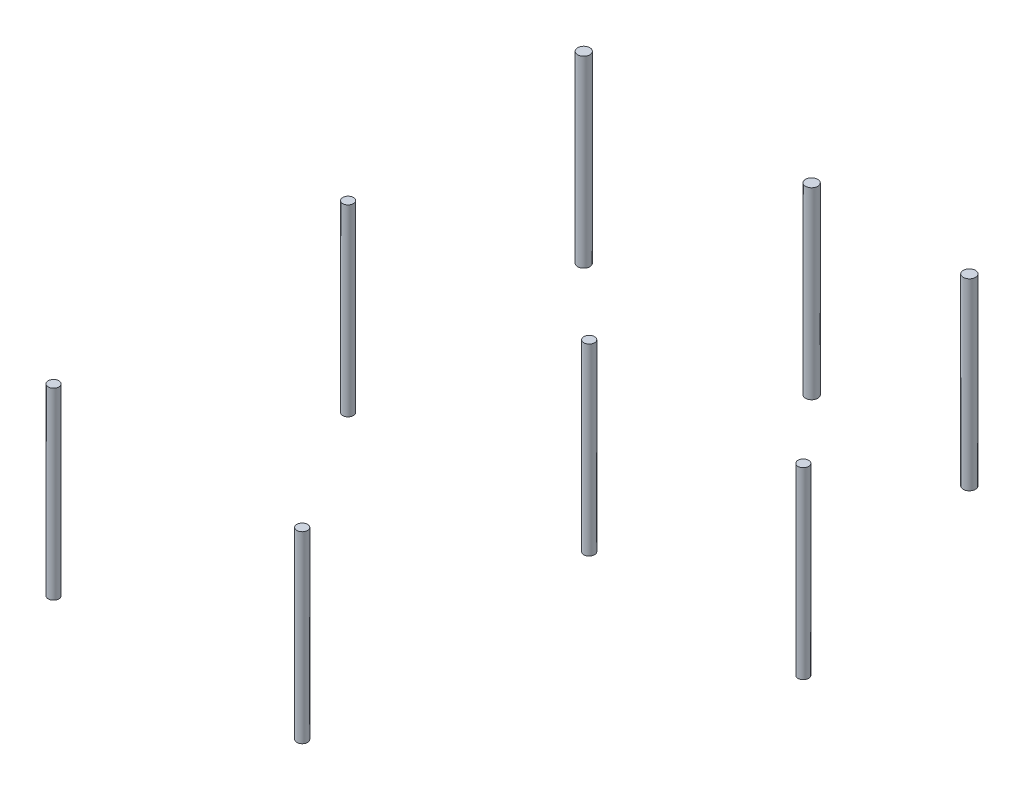
SolidWorks part; units mm, degrees
ref_plane "Front Plane" through (0, 0, 0) normal (0, 0, 1) x (1, 0, 0)
ref_plane "Top Plane" through (0, 0, 0) normal (0, 1, 0) x (1, 0, 0)
ref_plane "Right Plane" through (0, 0, 0) normal (1, 0, 0) x (0, 0, -1)
ref_plane "Plano2" through (0, 30, 0) normal (0, 1, 0) x (1, 0, 0)
sketch "Esboço2" plane through (0, 30, 0) normal (0, 1, 0) x (1, 0, 0)
  circle A5 centre (0, 693.0167) radius 8
  circle A6 centre (297.8704, 693.0167) radius 8
  circle A7 centre (504, 693.0167) radius 8
ref_plane "Plano1" through (0, 15, 0) normal (0, 1, 0) x (1, 0, 0)
sketch "Esboço6" plane through (0, 15, 0) normal (0, 1, 0) x (1, 0, 0)
  circle A0 centre (0, 385) radius 7
  circle A1 centre (315.1483, 385) radius 7
  circle A2 centre (595, 385) radius 7
sketch "Esboço7" plane through (0, 0, 0) normal (0, 1, 0) x (1, 0, 0)
  circle A0 centre (0, 0) radius 7
  circle A1 centre (325, 0) radius 7
extrude "Ressalto-extrusão2" add sketch "Esboço2" along normal blind 240
extrude "Ressalto-extrusão3" add sketch "Esboço6" along normal blind 240 separate body
extrude "Ressalto-extrusão4" add sketch "Esboço7" along normal blind 240 separate body
